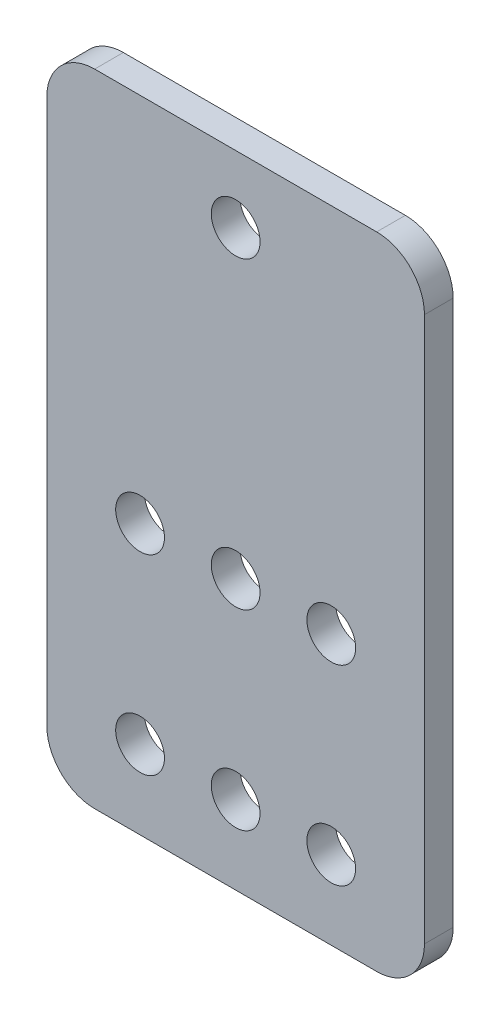
SolidWorks part; units mm, degrees
ref_plane "Front Plane" through (0, 0, 0) normal (0, 0, 1) x (1, 0, 0)
ref_plane "Top Plane" through (0, 0, 0) normal (0, 1, 0) x (1, 0, 0)
ref_plane "Right Plane" through (0, 0, 0) normal (1, 0, 0) x (0, 0, -1)
sketch "Sketch1" plane through (0, 0, 0) normal (0, 0, 1) x (1, 0, 0)
  line L1 (-14.75, -33.5) -> (14.75, -33.5)
  line L2 (-19.75, -28.5) -> (-19.75, 28.5)
  line L3 (-14.75, 33.5) -> (14.75, 33.5)
  line L4 (19.75, -28.5) -> (19.75, 28.5)
  line L5 (-19.75, -33.5) -> (19.75, 33.5) construction
  line L6 (-19.75, 33.5) -> (19.75, -33.5) construction
  circle A0 centre (10, -5.29) radius 2.55
  circle A1 centre (0, -5.29) radius 2.55
  circle A2 centre (-10, -5.29) radius 2.55
  circle A3 centre (0, -25.29) radius 2.55
  circle A4 centre (-10, -25.29) radius 2.55
  circle A5 centre (10, -25.29) radius 2.55
  circle A6 centre (0, 26.5) radius 2.55
  arc A7 (-14.75, -33.5) -> (-19.75, -28.5) centre (-14.75, -28.5) cw
  arc A8 (14.75, -33.5) -> (19.75, -28.5) centre (14.75, -28.5) ccw
  arc A9 (14.75, 33.5) -> (19.75, 28.5) centre (14.75, 28.5) cw
  arc A10 (-19.75, 28.5) -> (-14.75, 33.5) centre (-14.75, 28.5) cw
  point P0 (0, 0)
  dimension "D5" = 5.1
  dimension "D11" = 5
  dimension "D1" = 39.5
  dimension "D2" = 67
  dimension "D6" = 31.79
  dimension "D7" = 7
  dimension "D8" = 10
  dimension "D9" = 20
  dimension "D10" = 8.21
  dimension "D12" = 20
  dimension "D3" = 3
  dimension "D4" = 2
extrude "Boss-Extrude1" add sketch "Sketch1" along normal blind 3
